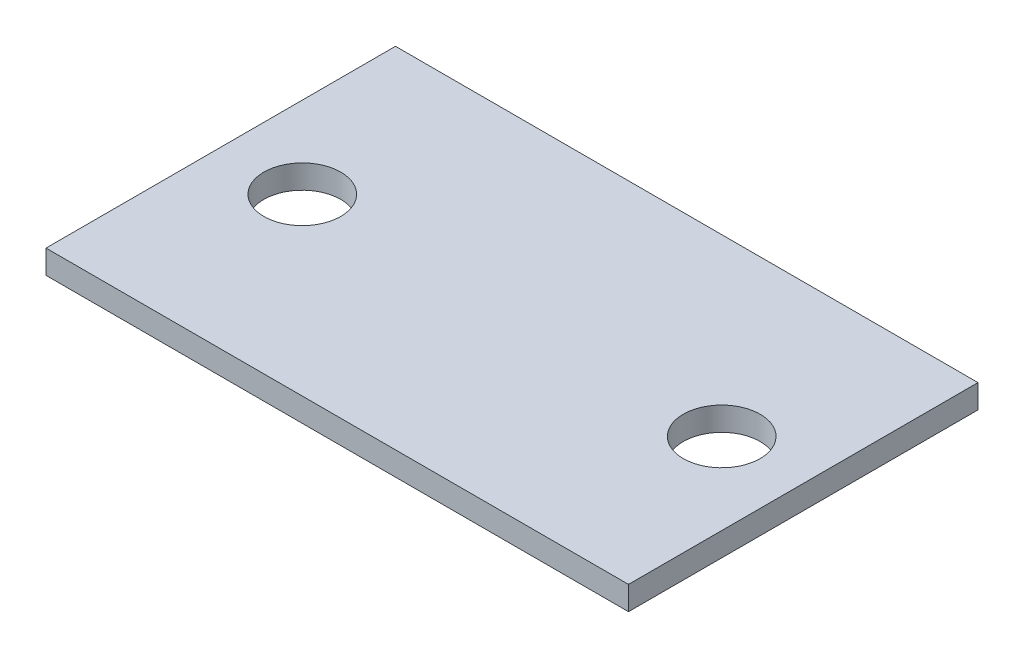
SolidWorks part; units mm, degrees
material "NEOPRENE"
ref_plane "Front Plane" through (0, 0, 0) normal (0, 0, 1) x (1, 0, 0)
ref_plane "Top Plane" through (0, 0, 0) normal (0, 1, 0) x (1, 0, 0)
ref_plane "Right Plane" through (0, 0, 0) normal (1, 0, 0) x (0, 0, -1)
sketch "Sketch1" plane through (0, 0, 0) normal (0, 1, 0) x (1, 0, 0)
  line L1 (-25, 15) -> (25, 15)
  line L2 (-25, 15) -> (-25, -15)
  line L3 (-25, -15) -> (25, -15)
  line L4 (25, 15) -> (25, -15)
  line L5 (-25, 15) -> (25, -15) construction
  line L6 (-25, -15) -> (25, 15) construction
  point P0 (0, 0)
  dimension "D1" = 50
  dimension "D2" = 30
extrude "Boss-Extrude1" add sketch "Sketch1" along normal blind 2.032
sketch "Sketch2" plane through (0, 2.032, 0) normal (0, 1, 0) x (1, 0, 0)
  line L0 (-25, 0) -> (25, 0) construction
  line L1 (-25, 15) -> (-25, -15) construction
  line L2 (25, -15) -> (25, 15) construction
  line L3 (0, 15) -> (0, -15) construction
  line L4 (25, 15) -> (-25, 15) construction
  line L5 (-25, -15) -> (25, -15) construction
  circle A0 centre (18, 0) radius 3.3
  circle A1 centre (-18, 0) radius 3.3
  dimension "D1" = 6.6
  dimension "D2" = 18
extrude "Cut-Extrude1" cut sketch "Sketch2" against normal through all
